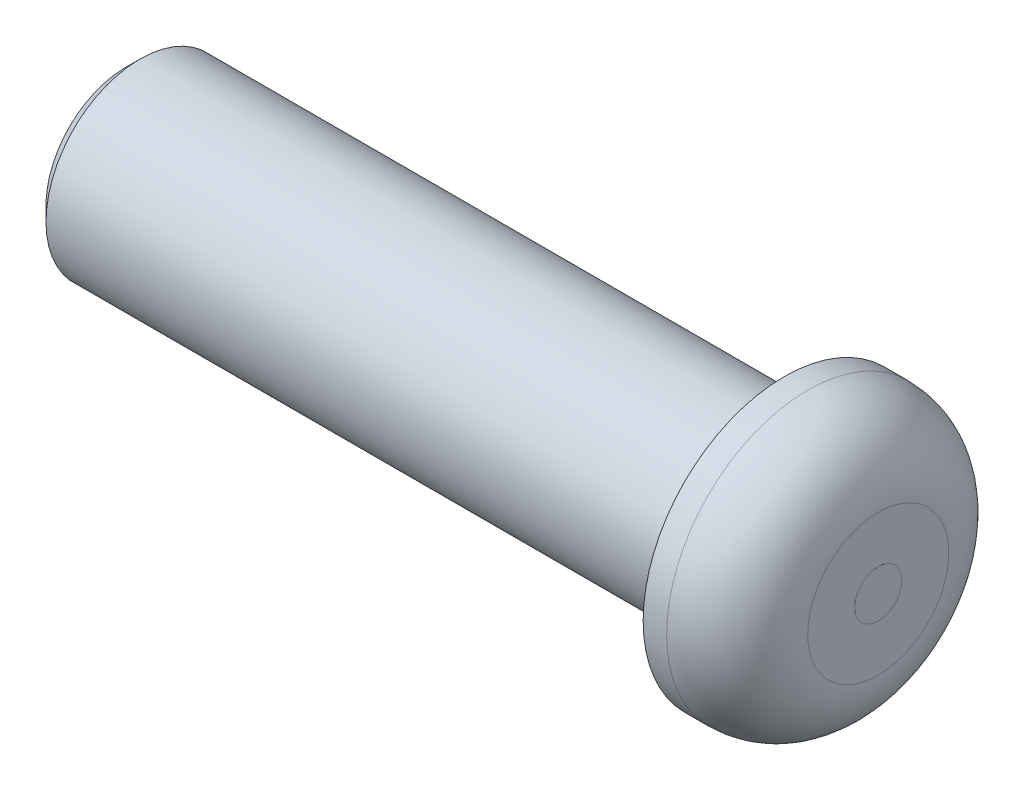
SolidWorks part; units mm, degrees
ref_plane "Plano frontal" through (0, 0, 0) normal (0, 0, 1) x (1, 0, 0)
ref_plane "Plano superior" through (0, 0, 0) normal (0, 1, 0) x (1, 0, 0)
ref_plane "Plano direito" through (0, 0, 0) normal (1, 0, 0) x (0, 0, -1)
sketch "Esboço1" plane through (0, 0, 0) normal (0, 0, 1) x (1, 0, 0)
  line L0 (0, 0) -> (16.0006, 0)
  line L1 (16, 0.5) -> (16, 3)
  line L2 (16, 3) -> (14, 3)
  line L3 (14, 3) -> (14, 2)
  line L4 (14, 2) -> (0, 2)
  line L5 (0, 2) -> (0, 0)
  line L9 (16, 0.5) -> (16.0006, 0.5)
  line L10 (16.0006, 0) -> (16.0006, 0.5)
  dimension "D1" = 2
  dimension "D2" = 1
  dimension "D3" = 2
revolve "Revolução1" add sketch "Esboço1" angle 360 about L0
fillet "Filete1" radius 1.5 1 edges at (16, 0, 3)
chamfer "Chanfro1" distance 0.3 angle 45 1 edges at (0, 0, 2)
